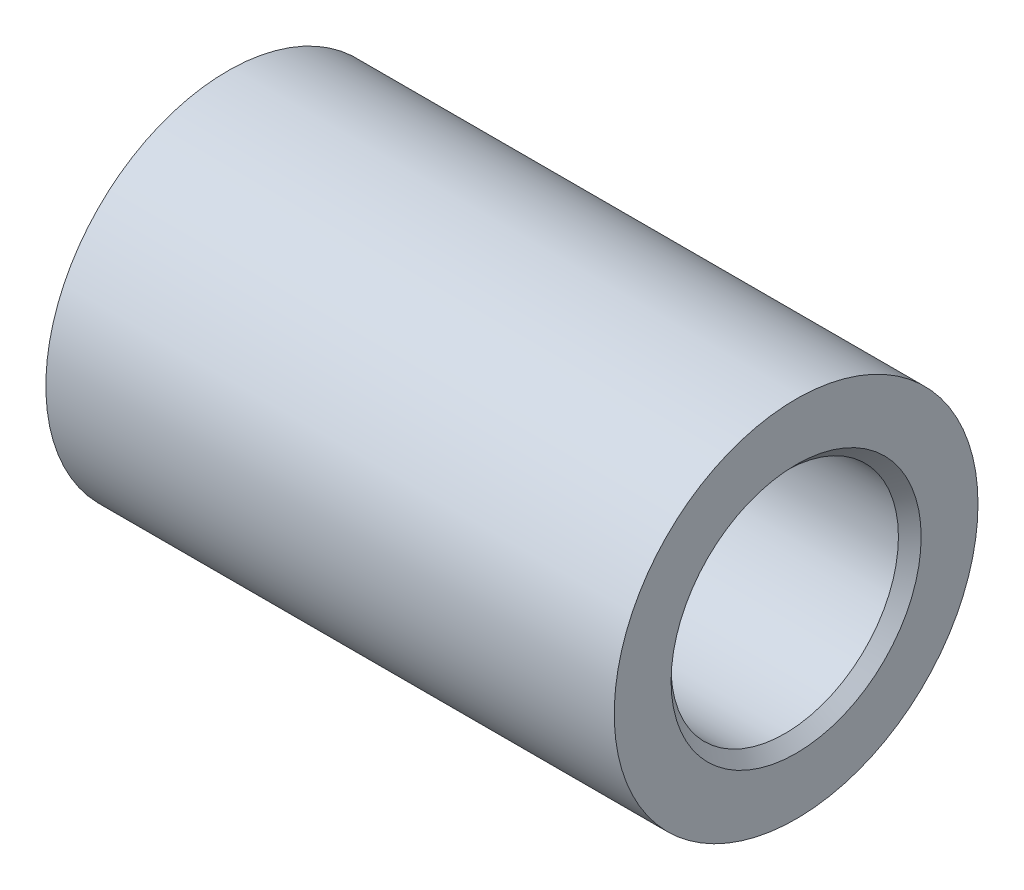
SolidWorks part; units mm, degrees
ref_plane "Ön Düzlem" through (0, 0, 0) normal (0, 0, 1) x (1, 0, 0)
ref_plane "Üst Düzlem" through (0, 0, 0) normal (0, 1, 0) x (1, 0, 0)
ref_plane "Sağ Düzlem" through (0, 0, 0) normal (1, 0, 0) x (0, 0, -1)
sketch "Sketch1" plane through (0, 0, 0) normal (0, 0, 1) x (1, 0, 0)
  line L0 (2.5759, 1.4204) -> (-2.4241, 1.4204)
  line L1 (-2.4241, 1.4204) -> (-2.4241, 0.9204)
  line L2 (-2.4241, 0.9204) -> (-2.3241, 0.8204)
  line L3 (-2.3241, 0.8204) -> (2.4759, 0.8204)
  line L4 (2.4759, 0.8204) -> (2.5759, 0.9204)
  line L5 (2.5759, 0.9204) -> (2.5759, 1.4204)
  line L6 (-2.5, -0.1796) -> (2.5, -0.1796) construction
  dimension "D1" = 5
  dimension "D2" = 1.6
  dimension "D3" = 1
  dimension "D4" = 90
  dimension "D5" = 0.5
revolve "Revolve1" add sketch "Sketch1" angle 360 about L6
